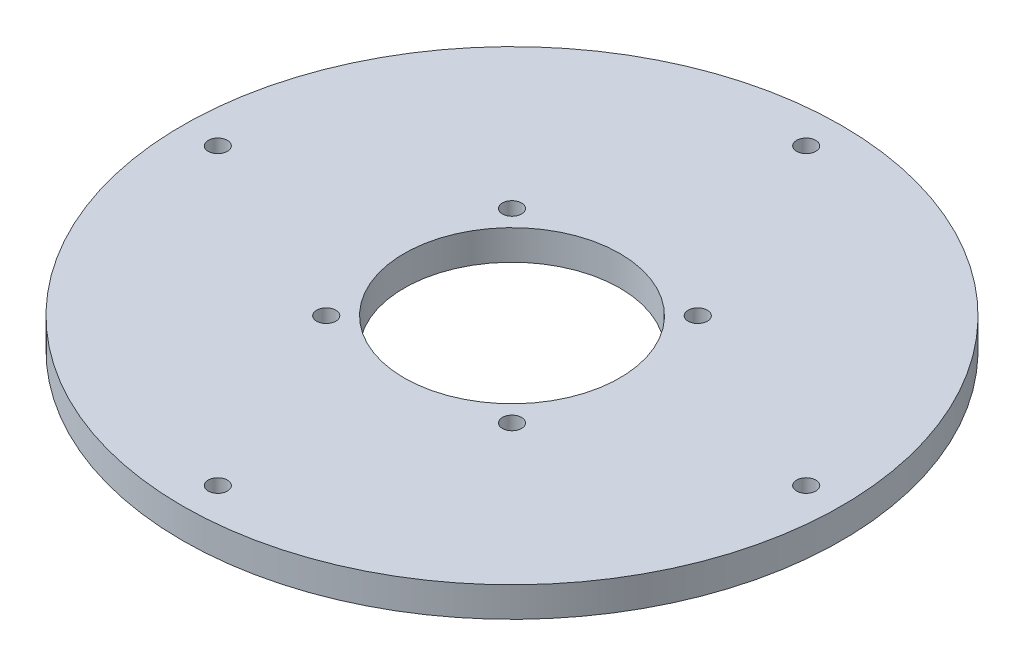
SolidWorks part; units mm, degrees
ref_plane "前视基准面" through (0, 0, 0) normal (0, 0, 1) x (1, 0, 0)
ref_plane "上视基准面" through (0, 0, 0) normal (0, 1, 0) x (1, 0, 0)
ref_plane "右视基准面" through (0, 0, 0) normal (1, 0, 0) x (0, 0, -1)
other "Configuration Table"
sketch "草图2" plane through (0, 0, 0) normal (0, 1, 0) x (1, 0, 0)
  line L1 (-23, -23) -> (23, -23)
  line L2 (-23, -23) -> (-23, 23)
  line L3 (-23, 23) -> (23, 23)
  line L4 (23, -23) -> (23, 23)
  line L5 (-23, -23) -> (23, 23) construction
  line L6 (-23, 23) -> (23, -23) construction
  circle A0 centre (0, 0) radius 18
extrude "凸台-拉伸1" add sketch "草图2" along normal blind 5
fillet "圆角1" radius 5.5 4 edges at (23, 2.5, 23) (23, 2.5, -23) (-23, 2.5, -23) (-23, 2.5, 23)
sketch "草图3" plane through (0, 5, 0) normal (0, 1, 0) x (1, 0, 0)
  line L1 (-15.5, -15.5) -> (15.5, -15.5)
  line L2 (-15.5, -15.5) -> (-15.5, 15.5)
  line L3 (-15.5, 15.5) -> (15.5, 15.5)
  line L4 (15.5, -15.5) -> (15.5, 15.5)
  line L5 (-15.5, -15.5) -> (15.5, 15.5) construction
  line L6 (-15.5, 15.5) -> (15.5, -15.5) construction
  circle A0 centre (-15.5, 15.5) radius 1.6
  circle A1 centre (15.5, 15.5) radius 1.6
  circle A2 centre (-15.5, -15.5) radius 1.6
  circle A3 centre (15.5, -15.5) radius 1.6
  point P0 (0, 0)
extrude "切除-拉伸1" cut sketch "草图3" against normal through all contours A2 | A0 | A1 | A3
sketch "草图4" plane through (0, 5, 0) normal (0, 1, 0) x (1, 0, 0)
  circle A1 centre (-49.1, 0) radius 1.6
  circle A2 centre (0, -49.1) radius 1.6
  circle A3 centre (49.1, 0) radius 1.6
  circle A4 centre (0, 49.1) radius 1.6
  circle A5 centre (0, 0) radius 55
  circle M3 centre (15.5, -15.5) radius 1.6
  circle M4 centre (15.5, 15.5) radius 1.6
  circle M5 centre (-15.5, 15.5) radius 1.6
  circle M6 centre (-15.5, -15.5) radius 1.6
  line M7 (-17.5, -23) -> (17.5, -23)
  arc M8 (17.5, -23) -> (23, -17.5) centre (17.5, -17.5) ccw
  line M9 (23, -17.5) -> (23, 17.5)
  arc M10 (23, 17.5) -> (17.5, 23) centre (17.5, 17.5) ccw
  line M11 (17.5, 23) -> (-17.5, 23)
  arc M12 (-17.5, 23) -> (-23, 17.5) centre (-17.5, 17.5) ccw
  line M13 (-23, 17.5) -> (-23, -17.5)
  arc M14 (-23, -17.5) -> (-17.5, -23) centre (-17.5, -17.5) ccw
  circle M15 centre (0, 0) radius 18
extrude "凸台-拉伸2" add sketch "草图4" against normal blind 5 contours M14 M7 M8 M9 M10 M11 M12 M13 M4 M6 M15 M5 M3 | A5 A1 A2 A3 A4 M7 M14 M13 M12 M11 M10 M9 M8
